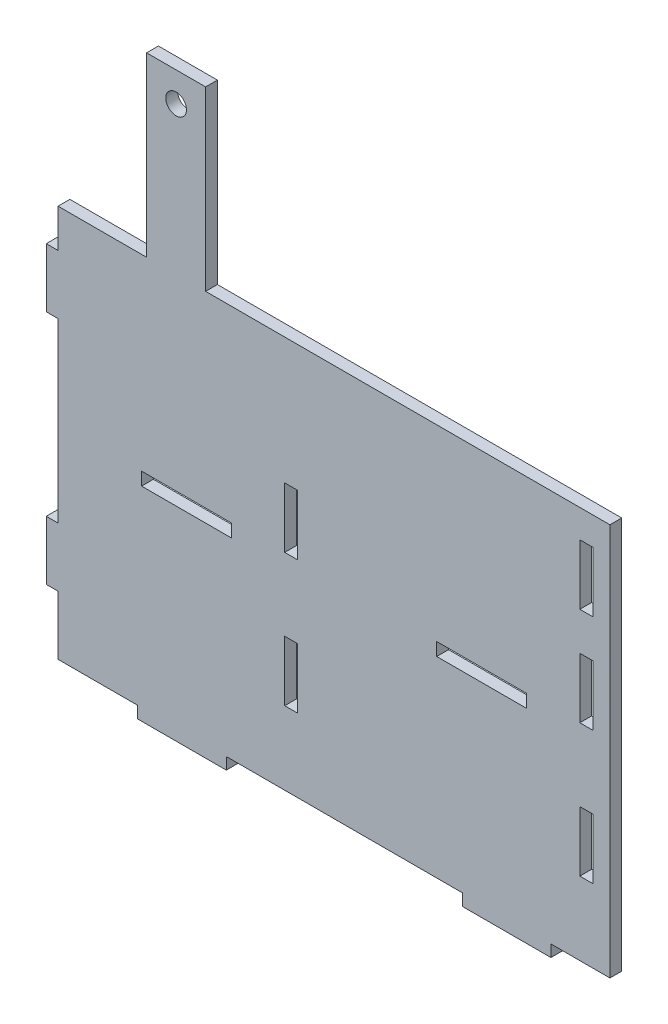
SolidWorks part; units mm, degrees
ref_plane "Спереди" through (0, 0, 0) normal (0, 0, 1) x (1, 0, 0)
ref_plane "Сверху" through (0, 0, 0) normal (0, 1, 0) x (1, 0, 0)
ref_plane "Справа" through (0, 0, 0) normal (1, 0, 0) x (0, 0, -1)
sketch "Эскиз1" plane through (0, 0, 0) normal (0, 0, 1) x (1, 0, 0)
  line L0 (0, 0) -> (0, 133)
  line L1 (0, 0) -> (187, 0)
  line L2 (187, 0) -> (187, 133)
  line L3 (187, 133) -> (0, 133)
  line L4 (93.5, 0) -> (93.5, 65) construction
  line L5 (176.8, 45.2) -> (181.2, 45.2)
  line L6 (176.8, 45.2) -> (176.8, 24.8)
  line L7 (176.8, 24.8) -> (181.2, 24.8)
  line L8 (181.2, 45.2) -> (181.2, 24.8)
  line L13 (187, 66.5) -> (146.4478, 66.5) construction
  line L14 (0, 66.5) -> (18.3539, 66.5) construction
  line L15 (0, 20) -> (-4, 20)
  line L16 (137, 0) -> (167, 0)
  line L17 (137, 0) -> (137, -4)
  line L18 (137, -4) -> (167, -4)
  line L19 (167, 0) -> (167, -4)
  line L20 (-4, 40) -> (-4, 20)
  line L21 (0, 40) -> (-4, 40)
  line L22 (0, 40) -> (0, 20)
  line L23 (57, -4) -> (27, -4)
  line L24 (27, 0) -> (27, -4)
  line L25 (57, 0) -> (27, 0)
  line L26 (57, 0) -> (57, -4)
  line L31 (-4, 100) -> (-4, 40) construction
  line L32 (-4, 100) -> (0, 100)
  line L33 (-4, 100) -> (-4, 120)
  line L34 (-4, 120) -> (0, 120)
  line L35 (0, 100) -> (0, 120)
  line L36 (42, 0) -> (42, -4) construction
  line L37 (152, 0) -> (152, -4) construction
  line L38 (-4, 30) -> (0, 30) construction
  line L39 (-4, 110) -> (0, 110) construction
  line L40 (93.5, 65) -> (58.7, 65) construction
  line L41 (93.5, 65) -> (128.3, 65) construction
  line L42 (43.5, 69.4) -> (43.5, 65) construction
  line L43 (58.7, 65) -> (28.3, 65)
  line L44 (58.7, 65) -> (58.7, 69.4)
  line L45 (58.7, 69.4) -> (28.3, 69.4)
  line L46 (28.3, 65) -> (28.3, 69.4)
  line L47 (128.3, 65) -> (158.7, 65)
  line L48 (128.3, 65) -> (128.3, 69.4)
  line L49 (128.3, 69.4) -> (158.7, 69.4)
  line L50 (158.7, 65) -> (158.7, 69.4)
  line L51 (143.5, 69.4) -> (143.5, 65) construction
  line L52 (179, 123.5) -> (179, 103.1) construction
  line L53 (181.2, 123.5) -> (176.8, 123.5)
  line L54 (181.2, 123.5) -> (181.2, 103.1)
  line L55 (181.2, 103.1) -> (176.8, 103.1)
  line L56 (176.8, 123.5) -> (176.8, 103.1)
  line L57 (181.2, 35) -> (176.8, 35) construction
  line L58 (179, 24.8) -> (179, 45.2) construction
  line L59 (181.2, 113.3) -> (176.8, 113.3) construction
  line L60 (181.2, 45.2) -> (181.2, 69.8) construction
  line L61 (181.2, 90.2) -> (176.8, 90.2)
  line L62 (181.2, 90.2) -> (181.2, 69.8)
  line L63 (181.2, 69.8) -> (176.8, 69.8)
  line L64 (176.8, 90.2) -> (176.8, 69.8)
  line L65 (181.2, 80) -> (176.8, 80) construction
  line L66 (40, 193) -> (40, 183) construction
  line L67 (50, 133) -> (30, 133)
  line L68 (50, 133) -> (50, 193)
  line L69 (50, 193) -> (30, 193)
  line L70 (30, 133) -> (30, 193)
  line L71 (176.8, 45.2) -> (76.8, 45.2) construction
  line L72 (76.8, 45.2) -> (76.8, 24.8)
  line L73 (76.8, 45.2) -> (81.2, 45.2)
  line L74 (81.2, 45.2) -> (81.2, 24.8)
  line L75 (76.8, 24.8) -> (81.2, 24.8)
  line L80 (76.8, 90.2) -> (76.8, 69.8)
  line L81 (81.2, 90.2) -> (76.8, 90.2)
  line L82 (81.2, 90.2) -> (81.2, 69.8)
  line L83 (81.2, 69.8) -> (76.8, 69.8)
  line L84 (76.8, 123.5) -> (76.8, 103.1) [skipped]
  line L85 (81.2, 123.5) -> (81.2, 103.1) [skipped]
  line L86 (81.2, 123.5) -> (76.8, 123.5) [skipped]
  line L87 (81.2, 103.1) -> (76.8, 103.1) [skipped]
  circle A0 centre (40, 183) radius 3.5
  point P73 (30, 163)
  dimension "D35" = 7
  dimension "D1" = 133
  dimension "D2" = 133
  dimension "D3" = 187
  dimension "D4" = 4.4
  dimension "D5" = 20.4
  dimension "D6" = 35
  dimension "D7" = 8
  dimension "D8" = 35
  dimension "D9" = 30
  dimension "D10" = 110
  dimension "D11" = 4
  dimension "D12" = 30
  dimension "D13" = 20
  dimension "D14" = 80
  dimension "D15" = 4
  dimension "D16" = 20
  dimension "D17" = 20
  dimension "D18" = 30.4
  dimension "D19" = 4.4
  dimension "D20" = 30.4
  dimension "D21" = 4.4
  dimension "D22" = 65
  dimension "D23" = 50
  dimension "D24" = 100
  dimension "D25" = 20.4
  dimension "D26" = 4.4
  dimension "D27" = 8
  dimension "D28" = 78.3
  dimension "D29" = 20.4
  dimension "D30" = 4.4
  dimension "D31" = 45
  dimension "D32" = 60
  dimension "D33" = 20
  dimension "D34" = 30
  dimension "D36" = 10
  dimension "D37" = 4
  dimension "D38" = 42
  dimension "D40" = 100
  dimension "D39" = 2
extrude "Бобышка-Вытянуть1" add sketch "Эскиз1" along normal blind 4 contours L26 L1 L24 L23 | L19 L1 L17 L18 | L2 L3 L0 L1 L50 L47 L48 L49 L5 L8 L7 L6 L43 L46 L45 L44 | L70 L3 L68 L69 A0 | L20 L15 L22 L21 | L33 L34 L35 L32
